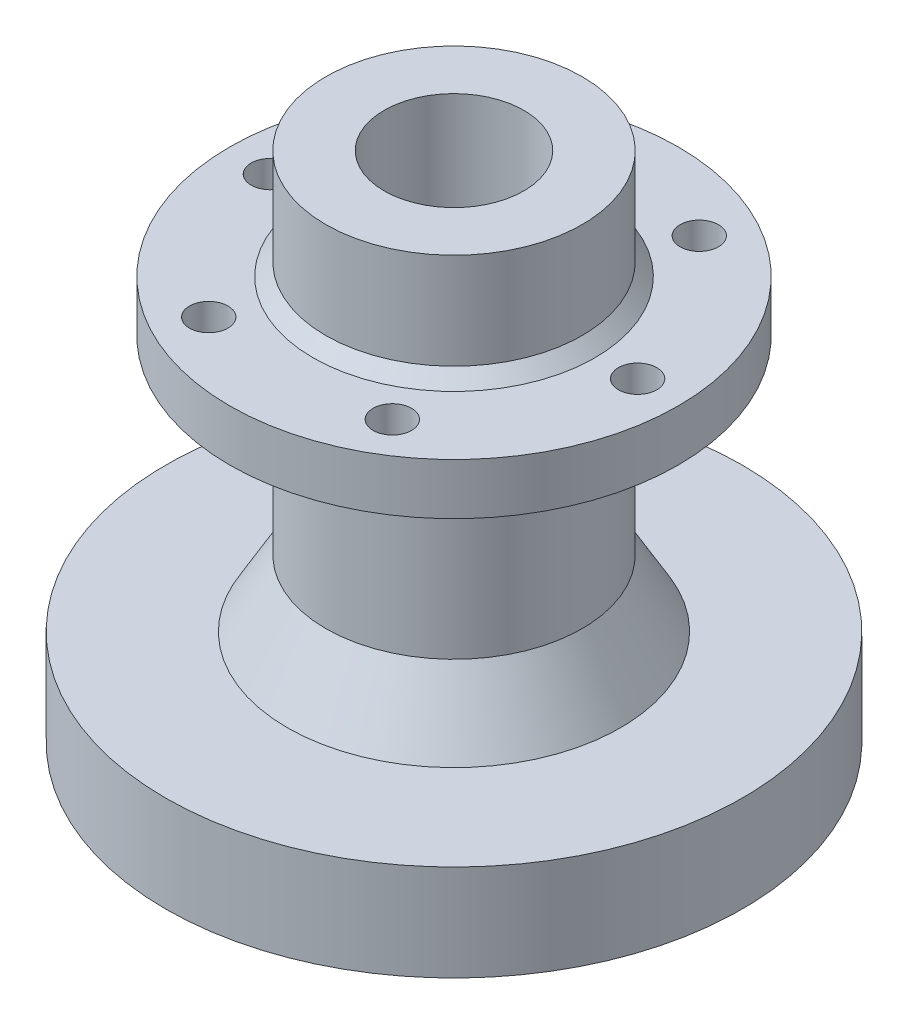
SolidWorks part; units mm, degrees
ref_plane "Спереди" through (0, 0, 0) normal (0, 0, 1) x (1, 0, 0)
ref_plane "Сверху" through (0, 0, 0) normal (0, 1, 0) x (1, 0, 0)
ref_plane "Справа" through (0, 0, 0) normal (1, 0, 0) x (0, 0, -1)
sketch "Эскиз1" plane through (0, 0, 0) normal (0, 1, 0) x (1, 0, 0)
  line L0 (-2, -6.7082) -> (-2, -8.85)
  line L1 (-2, -8.85) -> (2.5, -8.85)
  line L2 (2.5, -8.85) -> (2.5, -6.5383)
  circle A0 centre (0, 0) radius 45
  arc A1 (2.5, -6.5383) -> (-2, -6.7082) centre (0, 0) ccw
  dimension "D1" = 4.5
extrude "Вытянуть1" add sketch "Эскиз1" along normal blind 15
sketch "Эскиз2" plane through (0, 15, 0) normal (0, 1, 0) x (1, 0, 0)
  circle A0 centre (0, 0) radius 20
extrude "Вытянуть2" add sketch "Эскиз2" along normal blind 65
sketch "Эскиз4" plane through (0, 80, 0) normal (0, 1, 0) x (1, 0, 0)
  circle A0 centre (0, 0) radius 10.9
extrude "Вытянуть4" cut sketch "Эскиз4" against normal blind 52
ref_plane "Плоскость1" through (0, 55, 0) normal (0, 1, 0) x (-1, 0, 0)
sketch "Эскиз5" plane through (0, 55, 0) normal (0, 1, 0) x (-1, 0, 0)
  circle A0 centre (0, 0) radius 35
  circle A1 centre (0, 0) radius 10.9
extrude "Вытянуть5" add sketch "Эскиз5" along normal blind 8
chamfer "Фаска3" distance 2 angle 45 2 edges at (0, 55, 20) (0, 63, 20)
chamfer "Фаска4" distance 6 angle 60 1 edges at (0, 15, 20)
sketch "Эскиз6" plane through (0, 15, 0) normal (0, -1, 0) x (1, 0, 0)
  circle A0 centre (0, 0) radius 7
extrude "Вытянуть8" cut sketch "Эскиз6" against normal blind 4
sketch "Эскиз7" plane through (0, 63, 0) normal (0, 1, 0) x (1, 0, 0)
  circle A0 centre (-28.1542, -0.4999) radius 3
  circle A1 centre (-14.51, 24.1323) radius 3
  circle A2 centre (13.6441, 24.6322) radius 3
  circle A3 centre (28.1542, 0.4999) radius 3
  circle A4 centre (14.51, -24.1323) radius 3
  circle A5 centre (-13.6441, -24.6322) radius 3
extrude "Вырез-Вытянуть1" cut sketch "Эскиз7" against normal up to next
